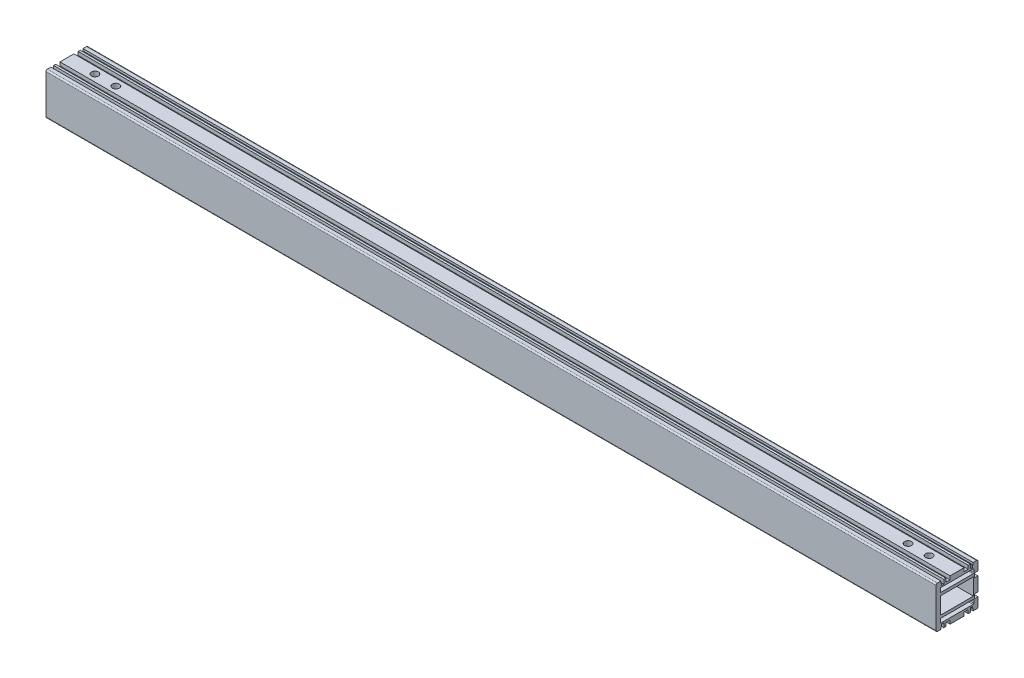
SolidWorks part; units mm, degrees
ref_plane "前视基准面" through (0, 0, 0) normal (0, 0, 1) x (1, 0, 0)
ref_plane "上视基准面" through (0, 0, 0) normal (0, 1, 0) x (1, 0, 0)
ref_plane "右视基准面" through (0, 0, 0) normal (1, 0, 0) x (0, 0, -1)
sketch "草图1" plane through (0, 0, 0) normal (1, 0, 0) x (0, 0, -1)
  line L0 (-15, 15) -> (15, -15) construction
  line L1 (-14, 15) -> (-11.5, 15)
  line L2 (-15, 14) -> (-15, -14)
  line L3 (-14, -15) -> (-11.5, -15)
  line L4 (15, 14) -> (15, 8)
  line L5 (15, 15) -> (-15, -15) construction
  line L6 (-11.5, 15) -> (-11.5, 13.5)
  line L7 (-11.5, 13.5) -> (-11.4, 13.5)
  line L8 (-11, 13.1) -> (-11, 12)
  line L9 (-11, 12) -> (-9.5, 12)
  line L10 (-9.5, 12) -> (-9.5, 15)
  line L11 (-9.5, 15) -> (-8, 15)
  line L12 (-8, 15) -> (-8, 12.5)
  line L13 (-8, 12.5) -> (-5, 12.5)
  line L14 (-5, 12.5) -> (-5, 15)
  line L15 (-5, 15) -> (5, 15)
  line L16 (0, 21.5201) -> (0, -18.309) construction
  line L17 (0, 55) -> (0, -55) construction
  line L18 (5, 12.5) -> (5, 15)
  line L19 (8, 12.5) -> (5, 12.5)
  line L20 (8, 15) -> (8, 12.5)
  line L21 (9.5, 15) -> (8, 15)
  line L22 (9.5, 12) -> (9.5, 15)
  line L23 (11, 12) -> (9.5, 12)
  line L24 (11, 13.1) -> (11, 12)
  line L25 (11.5, 13.5) -> (11.4, 13.5)
  line L26 (11.5, 15) -> (11.5, 13.5)
  line L27 (8, 15) -> (9.5, 15)
  line L28 (11.5, 15) -> (14, 15)
  line L29 (-19.8303, 0) -> (22.13, 0) construction
  line L30 (55, 0) -> (-55, 0) construction
  line L31 (8, -15) -> (9.5, -15)
  line L32 (11.5, -15) -> (11.5, -13.5)
  line L33 (11.5, -13.5) -> (11.4, -13.5)
  line L34 (11, -13.1) -> (11, -12)
  line L35 (11, -12) -> (9.5, -12)
  line L36 (9.5, -12) -> (9.5, -15)
  line L37 (9.5, -15) -> (8, -15)
  line L38 (8, -15) -> (8, -12.5)
  line L39 (8, -12.5) -> (5, -12.5)
  line L40 (5, -12.5) -> (5, -15)
  line L41 (-5, -15) -> (5, -15)
  line L42 (-5, -12.5) -> (-5, -15)
  line L43 (-8, -12.5) -> (-5, -12.5)
  line L44 (-8, -15) -> (-8, -12.5)
  line L45 (-9.5, -15) -> (-8, -15)
  line L46 (-9.5, -12) -> (-9.5, -15)
  line L47 (-11, -12) -> (-9.5, -12)
  line L48 (-11, -13.1) -> (-11, -12)
  line L49 (-11.5, -13.5) -> (-11.4, -13.5)
  line L50 (-11.5, -15) -> (-11.5, -13.5)
  line L51 (-9.5, -15) -> (-8, -15)
  line L52 (-5, -15) -> (5, -15)
  line L53 (8, -15) -> (9.5, -15)
  line L54 (11.5, -15) -> (14, -15)
  line L55 (15, 8) -> (12.5, 8)
  line L56 (12.5, 8) -> (12.5, 5)
  line L57 (12.5, 5) -> (15, 5)
  line L58 (12.5, -5) -> (15, -5)
  line L59 (12.5, -8) -> (12.5, -5)
  line L60 (15, -8) -> (12.5, -8)
  line L61 (15, 5) -> (15, -5)
  line L62 (15, -8) -> (15, -14)
  line L63 (12, -10.5) -> (12, -8.5)
  line L64 (-11.5, 11) -> (11.5, 11)
  line L65 (-12, 10.5) -> (-12, 8.5)
  line L66 (-11.5, 8) -> (11.5, 8)
  line L67 (12, 10.5) -> (12, 8.5)
  line L68 (-11.5, -8) -> (11.5, -8)
  line L69 (-12, -10.5) -> (-12, -8.5)
  line L70 (-11.5, -11) -> (11.5, -11)
  line L72 (-11.75, 6) -> (11.75, 6)
  line L73 (-11.75, 6) -> (-11.75, -6)
  line L74 (-11.75, -6) -> (11.75, -6)
  line L75 (11.75, 6) -> (11.75, -6)
  arc A0 (12, 8.5) -> (11.5, 8) centre (11.5, 8.5) cw
  arc A1 (11.5, 11) -> (12, 10.5) centre (11.5, 10.5) cw
  arc A2 (-11.5, 11) -> (-12, 10.5) centre (-11.5, 10.5) ccw
  arc A3 (-11.5, 8) -> (-12, 8.5) centre (-11.5, 8.5) cw
  arc A4 (-11, -13.1) -> (-11.4, -13.5) centre (-11.4, -13.1) cw
  arc A5 (11.4, -13.5) -> (11, -13.1) centre (11.4, -13.1) cw
  arc A6 (11.4, 13.5) -> (11, 13.1) centre (11.4, 13.1) ccw
  arc A7 (-11, 13.1) -> (-11.4, 13.5) centre (-11.4, 13.1) ccw
  arc A8 (-11.5, -8) -> (-12, -8.5) centre (-11.5, -8.5) ccw
  arc A9 (-11.5, -11) -> (-12, -10.5) centre (-11.5, -10.5) cw
  arc A10 (11.5, -11) -> (12, -10.5) centre (11.5, -10.5) ccw
  arc A11 (12, -8.5) -> (11.5, -8) centre (11.5, -8.5) ccw
  arc A12 (14, 15) -> (15, 14) centre (14, 14) cw
  arc A13 (14, -15) -> (15, -14) centre (14, -14) ccw
  arc A14 (-15, -14) -> (-14, -15) centre (-14, -14) ccw
  arc A15 (-15, 14) -> (-14, 15) centre (-14, 14) cw
  point P69 (12, 11)
  point P72 (-12, 11)
  point P77 (-11, -13.5)
  point P80 (11, -13.5)
  point P83 (11, 13.5)
  point P86 (-11, 13.5)
  point P99 (-12, -11)
  point P100 (12, -11)
  dimension "D17" = 0.5
  dimension "D18" = 0.4
  dimension "D21" = 1
  dimension "D1" = 3.5
  dimension "D2" = 1.5
  dimension "D3" = 0.5
  dimension "D4" = 1.5
  dimension "D5" = 3
  dimension "D6" = 30
  dimension "D7" = 30
  dimension "D8" = 1.5
  dimension "D9" = 2.5
  dimension "D10" = 3
  dimension "D11" = 2.5
  dimension "D12" = 7
  dimension "D13" = 3
  dimension "D14" = 4
  dimension "D15" = 3
  dimension "D16" = 24
  dimension "D19" = 23.5
  dimension "D20" = 12
extrude "凸台-拉伸1" add sketch "草图1" along normal mid plane 637 contours A15 L2 A14 L3 L50 L49 A4 L48 L47 L46 L45 L44 L43 L42 L41 L40 L39 L38 L31 L36 L35 L34 A5 L33 L32 L54 A13 L62 L60 L59 L58 L61 L57 L56 L55 L4 A12 L28 L26 L25 A6 L24 L23 L22 L21 L20 L19 L18 L15 L14 L13
hole_wizard "M6 螺纹孔1" positions "草图5" profile "草图4" tap size "M6" standard "GB"
sketch "草图5" plane through (0, 15, 0) normal (0, 1, 0) x (-1, 0, 0)
  line L0 (318.5, 5) -> (318.5, -5) construction
  line L1 (-318.5, -15) -> (318.5, -15) construction
  point P0 (298.5, 0)
  point P1 (283.5, 0)
  point P4 (-283.5, 0)
  point P7 (-298.5, 0)
  dimension "D1" = 20
  dimension "D2" = 15
sketch "草图4" plane through (-298.5, 15, 0) normal (1, 0, 0) x (0, 0, 1)
  line L0 (0, 0) -> (0, 16.5022)
  line L1 (0, 16.5022) -> (2.5, 15)
  line L2 (2.5, 15) -> (2.5, 0)
  line L5 (2.5, 0) -> (0, 0)
  line L10 (0, 16.5022) -> (-2.5, 15) construction
  line L11 (0, -6.35) -> (0, 107.95) construction
  dimension "螺纹孔钻头直径" = 5
  dimension "螺纹孔钻头深度" = 15
  dimension "导头角度" = 118
cosmetic thread "孔螺蚊线1" parameters "D1"=9, "D2"=6
cosmetic thread "孔螺蚊线2" parameters "D1"=9, "D2"=6
cosmetic thread "孔螺蚊线3" parameters "D1"=9, "D2"=6
cosmetic thread "孔螺蚊线4" parameters "D1"=9, "D2"=6
hole_wizard "M6 螺纹孔2" positions "草图7" profile "草图6" tap size "M6" standard "GB"
sketch "草图7" plane through (0, 0, -15) normal (0, 0, -1) x (-1, 0, 0)
  line L0 (318.5, 5) -> (318.5, -5) construction
  line L1 (-318.5, -15) -> (318.5, -15) construction
  point P0 (298.5, 0)
  point P1 (283.5, 0)
  dimension "D1" = 20
  dimension "D2" = 15
sketch "草图6" plane through (-298.5, 0, -15) normal (1, 0, 0) x (0, 1, 0)
  line L0 (0, 0) -> (0, 16.5022)
  line L1 (0, 16.5022) -> (2.5, 15)
  line L2 (2.5, 15) -> (2.5, 0)
  line L5 (2.5, 0) -> (0, 0)
  line L10 (0, 16.5022) -> (-2.5, 15) construction
  line L11 (0, -6.35) -> (0, 107.95) construction
  dimension "螺纹孔钻头直径" = 5
  dimension "螺纹孔钻头深度" = 15
  dimension "导头角度" = 118
cosmetic thread "孔螺蚊线5" parameters "D1"=3.25, "D2"=6
cosmetic thread "孔螺蚊线6" parameters "D1"=3.25, "D2"=6
hole_wizard "M4 螺纹孔1" positions "草图11" profile "草图10" tap size "M4" standard "GB"
sketch "草图11" plane through (0, 0, -15) normal (0, 0, -1) x (-1, 0, 0)
  line L0 (-318.5, 5) -> (-318.5, -5) construction
  line L1 (-318.5, -15) -> (318.5, -15) construction
  point P1 (-303.5, 0)
  point P3 (-118.5, 0)
  point P5 (1.5, 0)
  point P13 (98.5, 0)
  point P15 (248.5, 0)
  dimension "D1" = 15
  dimension "D2" = 15
  dimension "D3" = 185
  dimension "D4" = 15
  dimension "D5" = 120
  dimension "D6" = 15
  dimension "D7" = 150
  dimension "D8" = 97
  dimension "D9" = 15
  dimension "D10" = 15
sketch "草图10" plane through (303.5, 0, -15) normal (1, 0, 0) x (0, 1, 0)
  line L0 (0, 0) -> (0, 11.0914)
  line L1 (0, 11.0914) -> (1.65, 10.1)
  line L2 (1.65, 10.1) -> (1.65, 0)
  line L5 (1.65, 0) -> (0, 0)
  line L10 (0, 11.0914) -> (-1.65, 10.1) construction
  line L11 (0, -6.35) -> (0, 107.95) construction
  dimension "螺纹孔钻头直径" = 3.3
  dimension "螺纹孔钻头深度" = 10.1
  dimension "导头角度" = 118
cosmetic thread "孔螺蚊线7" parameters "D1"=3.25, "D2"=4
cosmetic thread "孔螺蚊线8" parameters "D1"=3.25, "D2"=4
cosmetic thread "孔螺蚊线9" parameters "D1"=3.25, "D2"=4
cosmetic thread "孔螺蚊线10" parameters "D1"=3.25, "D2"=4
cosmetic thread "孔螺蚊线11" parameters "D1"=3.25, "D2"=4
